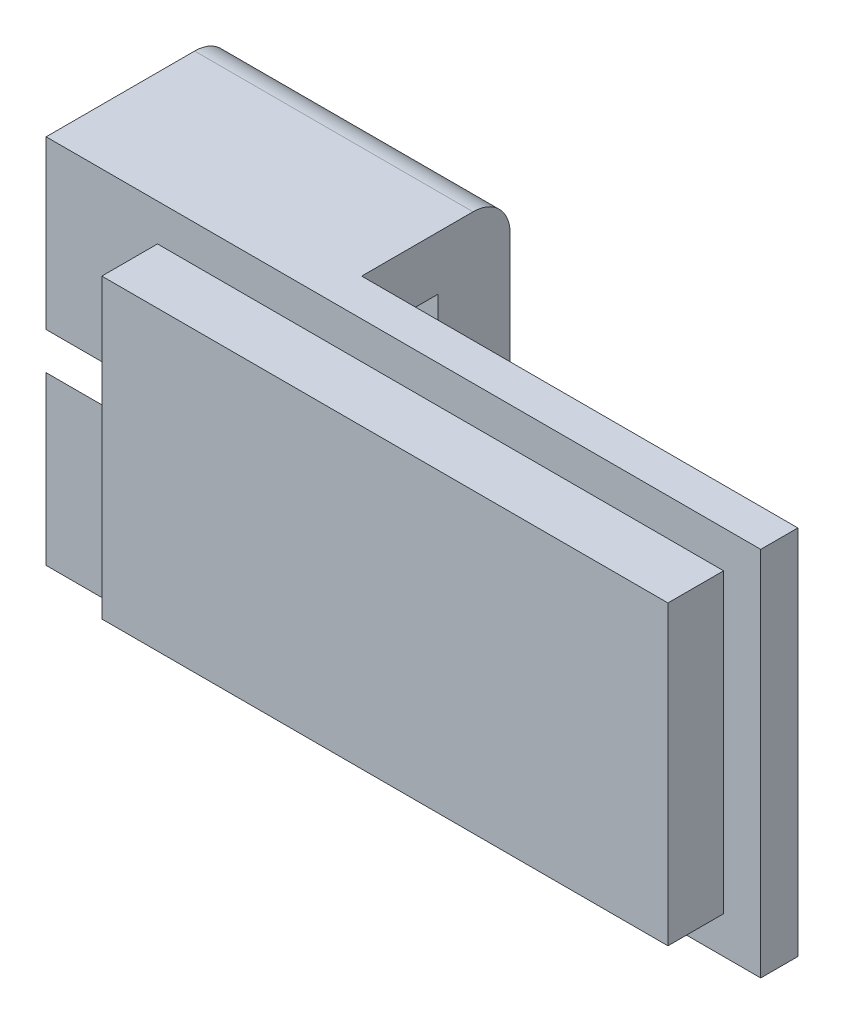
SolidWorks part; units mm, degrees
ref_plane "Front Plane" through (0, 0, 0) normal (1, 0, 0) x (0, 1, 0)
ref_plane "Top Plane" through (0, 0, 0) normal (0, 0, 1) x (0, 1, 0)
ref_plane "Right Plane" through (0, 0, 0) normal (0, 1, 0) x (-1, 0, 0)
sketch "Sketch1" plane through (0, 0, 0) normal (1, 0, 0) x (0, 1, 0)
  line L1 (-10, 5) -> (10, 5)
  line L2 (-10, 5) -> (-10, -5)
  line L3 (-10, -5) -> (10, -5)
  line L4 (10, 5) -> (10, -5)
  line L5 (-10, 5) -> (10, -5) construction
  line L6 (-10, -5) -> (10, 5) construction
  point P0 (0, 0)
  dimension "D1" = 10
  dimension "D2" = 20
extrude "Boss-Extrude1" add sketch "Sketch1" along normal blind 38.5
sketch "Sketch5" plane through (0, 0, 0) normal (0, 0, 1) x (0, 1, 0)
  line L1 (-8, -6) -> (8, -6)
  line L2 (-8, -6) -> (-8, -36.5)
  line L3 (-8, -36.5) -> (8, -36.5)
  line L4 (8, -6) -> (8, -36.5)
  line L5 (-10, -38.5) -> (-10, 0) construction
  line L6 (10, -38.5) -> (10, 0) construction
  line L7 (10, -38.5) -> (-10, -38.5) construction
  line L8 (10, 0) -> (-10, 0) construction
  dimension "D1" = 2
  dimension "D2" = 2
  dimension "D3" = 2
  dimension "D4" = 6
extrude "Boss-Extrude2" add sketch "Sketch5" along normal blind 8
sketch "Sketch2" plane through (0, 0, 0) normal (1, 0, 0) x (0, 1, 0)
  circle A0 centre (0, 0) radius 5.1
  dimension "D1" = 10.2
extrude "Cut-Extrude3" cut sketch "Sketch2" along normal blind 10
fillet "Fillet1" radius 2 2 edges at (19.25, -10, -5) (19.25, 10, -5)
sketch "Sketch6" plane through (0, 0, -5) normal (0, 0, -1) x (1, 0, 0)
  line L0 (0, 10) -> (38.5, 10) construction
  line L1 (15, 10) -> (38.5, 10)
  line L2 (15, 10) -> (15, -10)
  line L3 (15, -10) -> (38.5, -10)
  line L4 (38.5, 10) -> (38.5, -10)
  line L5 (10, 5.1) -> (10, -5.1) construction
  dimension "D1" = 5
extrude "Cut-Extrude4" cut sketch "Sketch6" against normal blind 8
sketch "Sketch7" plane through (15, 0, 0) normal (1, 0, 0) x (0, 1, 0)
  line L0 (0, 0) -> (6, 0) construction
  line L1 (0, -7.15) -> (0, 7.15) construction
  line L2 (4.9, 1.1) -> (7.1, 1.1)
  line L3 (4.9, 1.1) -> (4.9, -1.1)
  line L4 (4.9, -1.1) -> (7.1, -1.1)
  line L5 (7.1, 1.1) -> (7.1, -1.1)
  line L6 (4.9, 1.1) -> (7.1, -1.1) construction
  line L7 (4.9, -1.1) -> (7.1, 1.1) construction
  line L8 (-4.9, -1.1) -> (-7.1, -1.1)
  line L9 (-7.1, 1.1) -> (-7.1, -1.1)
  line L10 (-4.9, 1.1) -> (-7.1, 1.1)
  line L11 (-4.9, 1.1) -> (-4.9, -1.1)
  dimension "D1" = 6
  dimension "D2" = 2.2
  dimension "D3" = 2.2
extrude "Cut-Extrude5" cut sketch "Sketch7" against normal blind 3
